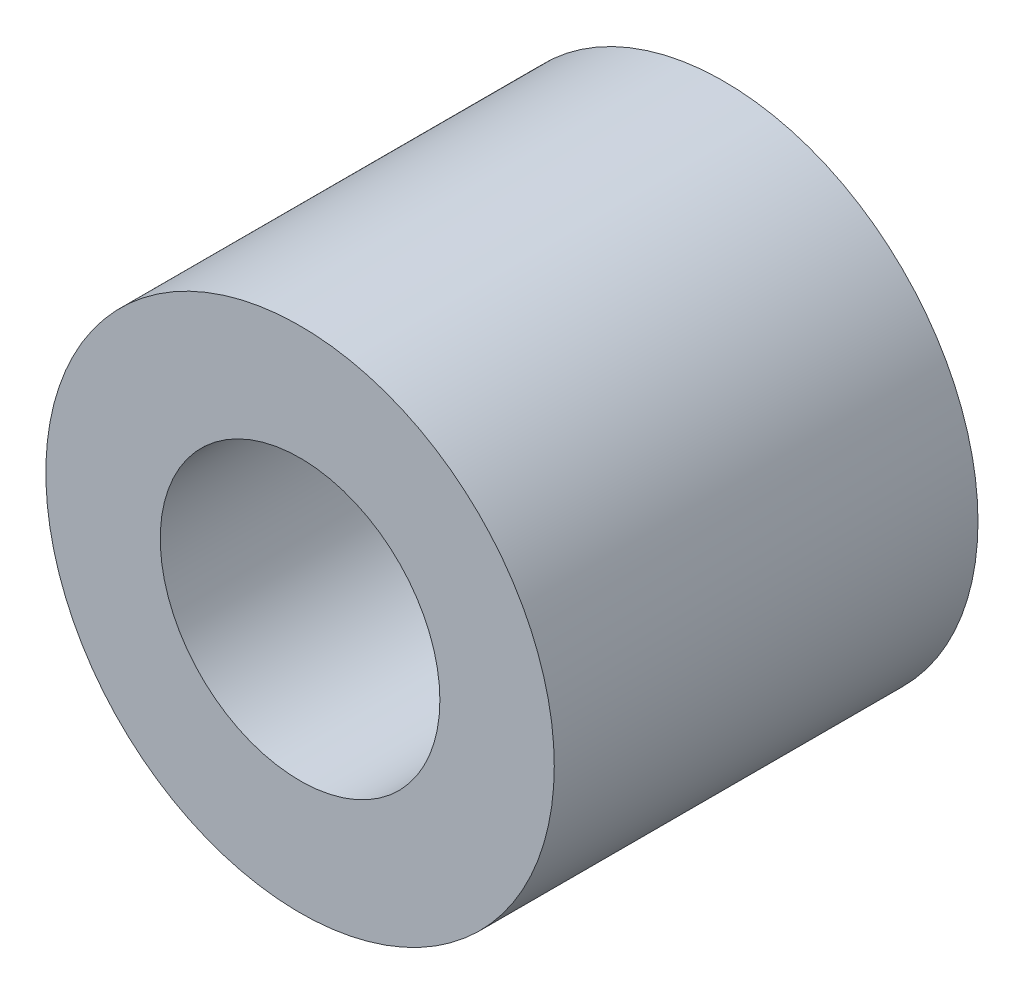
SolidWorks part; units mm, degrees
ref_plane "Спереди" through (0, 0, 0) normal (0, 0, 1) x (1, 0, 0)
ref_plane "Сверху" through (0, 0, 0) normal (0, 1, 0) x (1, 0, 0)
ref_plane "Справа" through (0, 0, 0) normal (1, 0, 0) x (0, 0, -1)
sketch "Эскиз1" plane through (0, 0, 0) normal (0, 0, 1) x (1, 0, 0)
  circle A0 centre (0, 0) radius 3
  circle A1 centre (0, 0) radius 1.65
  dimension "D1" = 6
  dimension "D2" = 3.3
extrude "Бобышка-Вытянуть1" add sketch "Эскиз1" along normal blind 5
